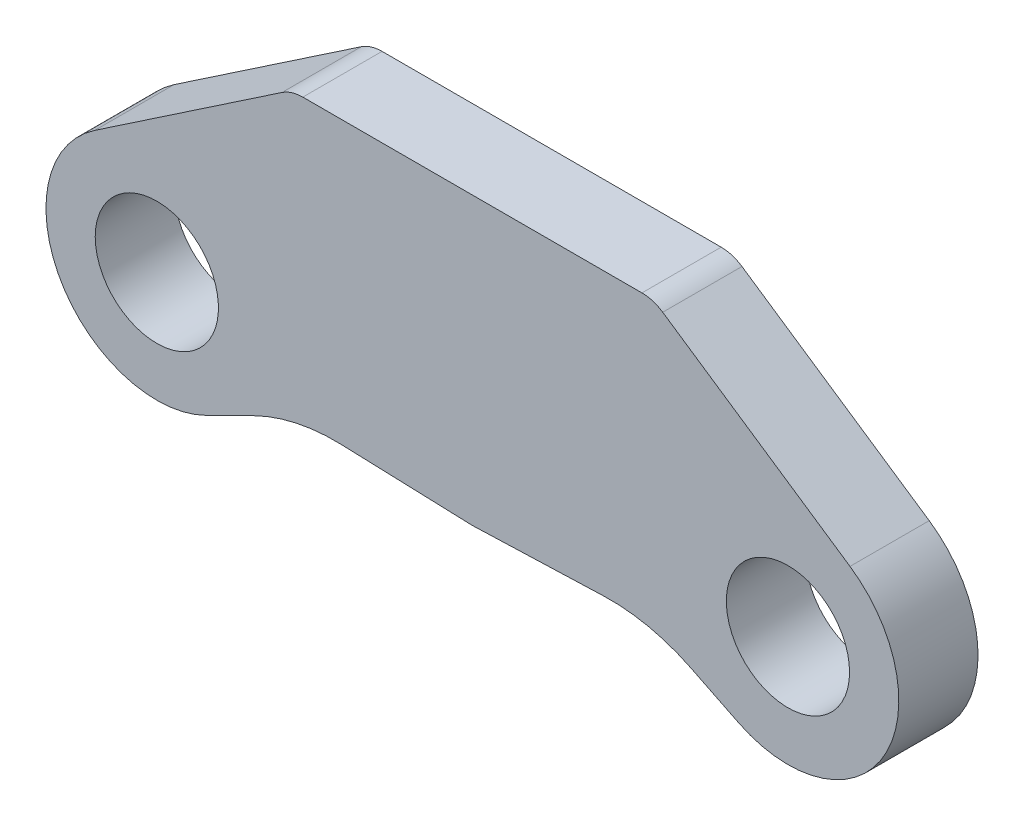
SolidWorks part; units mm, degrees
ref_plane "Front Plane" through (0, 0, 0) normal (0, 0, 1) x (1, 0, 0)
ref_plane "Top Plane" through (0, 0, 0) normal (0, 1, 0) x (1, 0, 0)
ref_plane "Right Plane" through (0, 0, 0) normal (1, 0, 0) x (0, 0, -1)
sketch "Sketch1" plane through (0, 0, 0) normal (0, 0, 1) x (1, 0, 0)
  line L2 (0, 19.0521) -> (21.3995, 19.0521)
  line L3 (0, 0) -> (0, 19.0521)
  line L4 (24.0234, 18.2491) -> (47.6576, 2.2872)
  line L5 (33.6267, -21.8489) -> (27.6054, -18.8721)
  line L6 (16.5562, -16.4925) -> (0, -17.0707)
  line L7 (0, -17.0707) -> (0, 0)
  circle A1 centre (39.8272, -9.3071) radius 7.7757
  arc A2 (21.3995, 19.0521) -> (24.0234, 18.2491) centre (21.3995, 14.3641) cw
  arc A3 (47.6576, 2.2872) -> (33.6267, -21.8489) centre (39.8272, -9.3071) cw
  arc A4 (27.6054, -18.8721) -> (16.5562, -16.4925) centre (17.3629, -39.5897) ccw
  point P0 (0, -0.7222)
extrude "Boss-Extrude1" add sketch "Sketch1" along normal blind 10
mirror "Mirror1" about plane through (0, 0, 10) normal (1, 0, 0) of "Boss-Extrude1"
